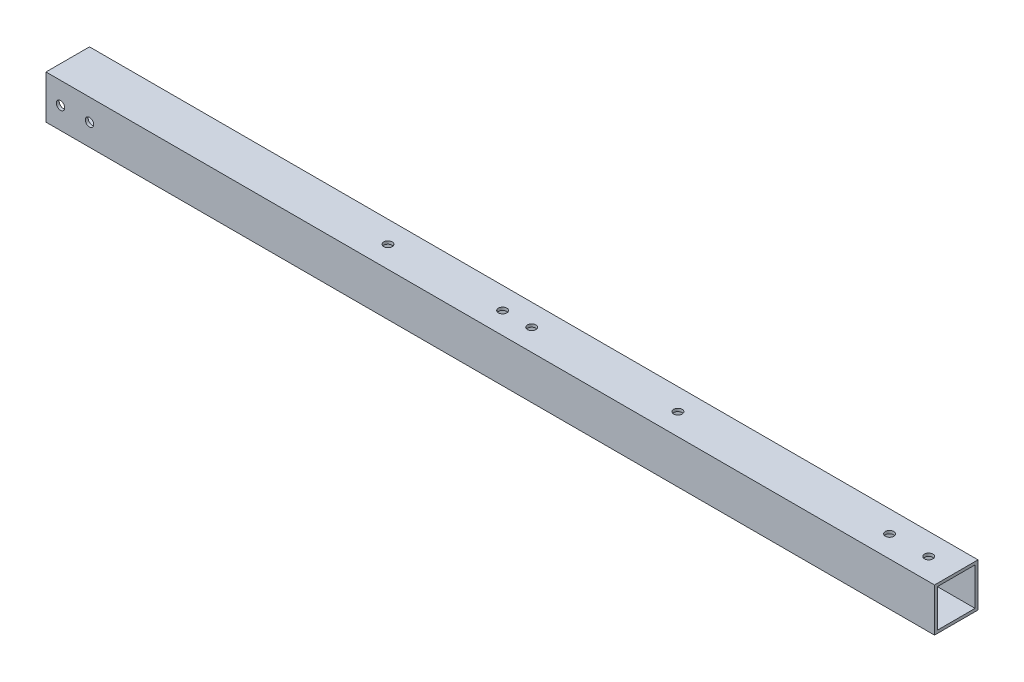
SolidWorks part; units mm, degrees
material "Thornel Mat VMA"
ref_plane "前视基准面" through (0, 0, 0) normal (0, 0, 1) x (1, 0, 0)
ref_plane "上视基准面" through (0, 0, 0) normal (0, 1, 0) x (1, 0, 0)
ref_plane "右视基准面" through (0, 0, 0) normal (1, 0, 0) x (0, 0, -1)
other "Configuration Table"
sketch "草图1" plane through (0, 0, 0) normal (1, 0, 0) x (0, 0, -1)
  line L0 (-6.5, -6.5) -> (-6.5, 6.5)
  line L1 (-7.5, -7.5) -> (7.5, -7.5)
  line L2 (-7.5, -7.5) -> (-7.5, 7.5)
  line L3 (-7.5, 7.5) -> (7.5, 7.5)
  line L4 (7.5, -7.5) -> (7.5, 7.5)
  line L5 (-7.5, -7.5) -> (7.5, 7.5) construction
  line L6 (-7.5, 7.5) -> (7.5, -7.5) construction
  line L7 (-6.5, 6.5) -> (6.5, 6.5)
  line L8 (6.5, -6.5) -> (6.5, 6.5)
  line L9 (-6.5, -6.5) -> (6.5, -6.5)
  point P0 (0, 0)
  dimension "D1" = 15
  dimension "D2" = 15
  dimension "D3" = 1
extrude "凸台-拉伸1" add sketch "草图1" along normal blind 306.44
sketch "草图2" plane through (0, -7.5, 0) normal (0, -1, 0) x (1, 0, 0)
  line L0 (0, 0) -> (352.5026, 0) construction
  line L1 (0, 19.5) -> (0, -19.5) construction
  circle A0 centre (110.44, 0) radius 1.45 construction
  circle A1 centre (210.44, 0) radius 1.45 construction
  circle A2 centre (110.44, 0) radius 1.45
  circle A3 centre (210.44, 0) radius 1.45
  circle A4 centre (283.44, 0) radius 1.45 construction
  circle A5 centre (296.94, 0) radius 1.45 construction
  circle A6 centre (283.44, 0) radius 1.45
  circle A7 centre (296.94, 0) radius 1.45
  circle A8 centre (150, 0) radius 1.45
  circle A9 centre (160, 0) radius 1.45
  dimension "D2" = 160
  dimension "D3" = 2.9
  dimension "D1" = 150
extrude "切除-拉伸1" cut sketch "草图2" against normal through all
sketch "草图3" plane through (0, 0, -7.5) normal (0, 0, -1) x (-1, 0, 0)
  circle A0 centre (-5, 0) radius 1.45 construction
  circle A1 centre (-15, 0) radius 1.45 construction
  circle A2 centre (-5, 0) radius 1.45
  circle A3 centre (-15, 0) radius 1.45
extrude "切除-拉伸2" cut sketch "草图3" against normal through all
